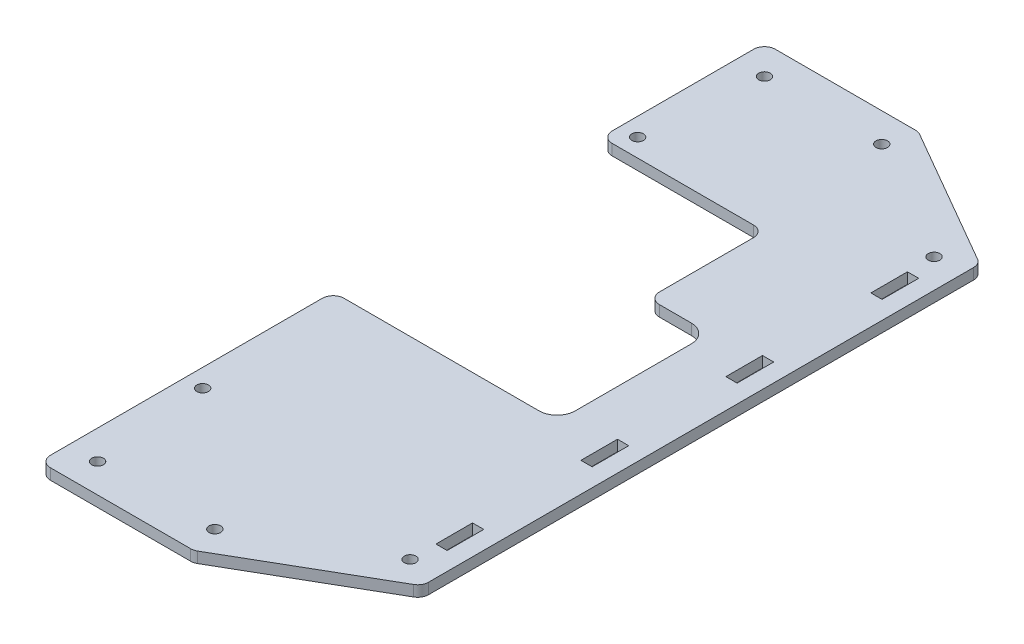
SolidWorks part; units mm, degrees
ref_plane "Front Plane" through (0, 0, 0) normal (0, 0, 1) x (1, 0, 0)
ref_plane "Top Plane" through (0, 0, 0) normal (0, 1, 0) x (1, 0, 0)
ref_plane "Right Plane" through (0, 0, 0) normal (1, 0, 0) x (0, 0, -1)
sketch "Sketch1" plane through (0, 0, 0) normal (0, 1, 0) x (1, 0, 0)
  line L0 (-85, 100) -> (85, 100) construction
  line L1 (-125, 100) -> (125, 100) construction
  line L2 (-125, 100) -> (-125, -100) construction
  line L3 (-125, -100) -> (125, -100) construction
  line L4 (125, 100) -> (125, -100) construction
  line L5 (85, 100) -> (125, 76.906) construction
  line L6 (125, 76.906) -> (125, -76.906) construction
  line L8 (-125, -76.906) -> (-125, 76.906) construction
  line L9 (-125, 76.906) -> (-85, 100) construction
  line L10 (-125, 0) -> (125, 0) construction
  line L11 (85, -100) -> (125, -76.906) construction
  line L12 (-85, -100) -> (85, -100) construction
  line L13 (-125, -76.906) -> (-85, -100) construction
  line L15 (-42.5, 100) -> (42.5, 100) construction
  line L16 (-42.5, 100) -> (-42.5, 65) construction
  line L17 (-42.5, 65) -> (42.5, 65) construction
  line L18 (42.5, 100) -> (42.5, 65) construction
  line L19 (42.5, -100) -> (42.5, -65) construction
  line L20 (-42.5, -65) -> (42.5, -65) construction
  line L21 (-42.5, -100) -> (-42.5, -65) construction
  line L22 (-42.5, -100) -> (42.5, -100) construction
  line L23 (42.5, 100) -> (85, 100)
  line L24 (85, 100) -> (125, 76.906)
  line L25 (125, 76.906) -> (125, -76.906)
  line L26 (125, -76.906) -> (85, -100)
  line L27 (85, -100) -> (42.5, -100)
  line L28 (42.5, 100) -> (42.5, -100)
  line L29 (99.3, 22) -> (67.3, 22) construction
  line L30 (103.3, -14) -> (103.3, 18) construction
  line L31 (63.3, 18) -> (63.3, -14) construction
  line L32 (67.3, -18) -> (99.3, -18) construction
  line L33 (99.3, 22) -> (67.3, 22) construction
  line L34 (103.3, -14) -> (103.3, 18) construction
  line L35 (63.3, 18) -> (63.3, -14) construction
  line L36 (67.3, -18) -> (99.3, -18) construction
  line L37 (99.3, 23) -> (67.3, 23)
  line L38 (62.3, 18) -> (62.3, -14)
  line L39 (67.3, -19) -> (99.3, -19)
  line L40 (104.3, -14) -> (104.3, 18)
  arc A0 (67.3, 22) -> (63.3, 18) centre (67.3, 18) ccw construction
  arc A1 (103.3, 18) -> (99.3, 22) centre (99.3, 18) ccw construction
  arc A2 (63.3, -14) -> (67.3, -18) centre (67.3, -14) ccw construction
  arc A3 (99.3, -18) -> (103.3, -14) centre (99.3, -14) ccw construction
  arc A4 (103.3, 18) -> (99.3, 22) centre (99.3, 18) ccw construction
  arc A5 (67.3, 22) -> (63.3, 18) centre (67.3, 18) ccw construction
  arc A6 (63.3, -14) -> (67.3, -18) centre (67.3, -14) ccw construction
  arc A7 (99.3, -18) -> (103.3, -14) centre (99.3, -14) ccw construction
  arc A8 (104.3, 18) -> (99.3, 23) centre (99.3, 18) ccw
  arc A9 (67.3, 23) -> (62.3, 18) centre (67.3, 18) ccw
  arc A10 (62.3, -14) -> (67.3, -19) centre (67.3, -14) ccw
  arc A11 (99.3, -19) -> (104.3, -14) centre (99.3, -14) ccw
  point P4 (0, 100)
  point P6 (-125, 0)
  point P9 (0, 0)
  point P22 (0, 65)
  dimension "D1" = 250
  dimension "D2" = 200
  dimension "D3" = 60
  dimension "D4" = 60
  dimension "D5" = 40
  dimension "D6" = 85
  dimension "D7" = 35
  dimension "D8" = 1
extrude "Boss-Extrude1" add sketch "Sketch1" along normal blind 3
sketch "Sketch2" plane through (0, 3, 0) normal (0, 1, 0) x (1, 0, 0)
  line L0 (42.5, 100) -> (42.5, -100) construction
  line L1 (42.5, 55) -> (87.5, 55)
  line L2 (42.5, 55) -> (42.5, -19)
  line L3 (42.5, -19) -> (87.5, -19)
  line L4 (87.5, 55) -> (87.5, -19)
  line L5 (67.3, -19) -> (99.3, -19) construction
  dimension "D1" = 74
  dimension "D2" = 45
extrude "Cut-Extrude1" cut sketch "Sketch2" against normal up to next
fillet "Fillet2" radius 3 10 edges at (42.5, 1.5, 19) (42.5, 1.5, 100) (85, 1.5, 100) (125, 1.5, 76.906) (125, 1.5, -76.906) (85, 1.5, -100) (42.5, 1.5, -100) (87.5, 1.5, -55) (42.5, 1.5, -55) (87.5, 1.5, -23)
sketch "Sketch3" plane through (0, 3, 0) normal (0, 1, 0) x (1, 0, 0)
  line L0 (118.45, 14.95) -> (118.45, -14.95) construction
  line L5 (116.9, 14.95) -> (120, 14.95)
  line L6 (116.9, 14.95) -> (116.9, 25.05)
  line L7 (116.9, 25.05) -> (120, 25.05)
  line L8 (120, 14.95) -> (120, 25.05)
  line L9 (116.9, -14.95) -> (120, -14.95)
  line L10 (116.9, -14.95) -> (116.9, -25.05)
  line L11 (116.9, -25.05) -> (120, -25.05)
  line L12 (120, -14.95) -> (120, -25.05)
  line L13 (125, -75.1739) -> (125, 75.1739) construction
  line L14 (116.9, 65.05) -> (120, 65.05)
  line L15 (116.9, 65.05) -> (116.9, 54.95)
  line L16 (116.9, 54.95) -> (120, 54.95)
  line L17 (120, 65.05) -> (120, 54.95)
  line L18 (116.9, -54.95) -> (120, -54.95)
  line L19 (116.9, -54.95) -> (116.9, -65.05)
  line L20 (116.9, -65.05) -> (120, -65.05)
  line L21 (120, -54.95) -> (120, -65.05)
  point P0 (120, 20)
  point P1 (120, -20)
  point P21 (120, 60)
  point P22 (120, -60)
  point P25 (118.45, 0)
  dimension "D1" = 40
  dimension "D2" = 40
  dimension "D3" = 3.1
  dimension "D4" = 10.1
  dimension "D5" = 5
  dimension "D6" = 40
extrude "Cut-Extrude2" cut sketch "Sketch3" against normal through all
sketch "Sketch4" plane through (0, 3, 0) normal (0, 1, 0) x (1, 0, 0)
  line L0 (84.1962, 100) -> (45.5, 100) construction
  line L1 (42.5, 97) -> (42.5, 58) construction
  line L2 (84.5, 55) -> (45.5, 55) construction
  line L4 (42.5, -22) -> (42.5, -97) construction
  line L5 (45.5, -100) -> (84.1962, -100) construction
  line L6 (125, -75.1739) -> (125, 75.1739) construction
  line L7 (123.5, 77.772) -> (85.6962, 99.5981) construction
  line L8 (85.6962, -99.5981) -> (123.5, -77.772) construction
  circle A0 centre (50.5, 92) radius 1.6
  circle A1 centre (47.5, 60) radius 1.6
  circle A2 centre (47.5, -60) radius 1.6
  circle A3 centre (50.5, -92) radius 1.6
  circle A4 centre (117, 72.2872) radius 1.6
  circle A5 centre (117, -72.2872) radius 1.6
  circle A6 centre (82.8564, 92) radius 1.6
  circle A7 centre (82.8564, -92) radius 1.6
  dimension "D1" = 3.2
  dimension "D2" = 8
  dimension "D3" = 8
  dimension "D4" = 5
  dimension "D5" = 5
  dimension "D6" = 5
  dimension "D7" = 40
  dimension "D8" = 8
  dimension "D9" = 8
  dimension "D10" = 8
  dimension "D11" = 8
  dimension "D12" = 8
  dimension "D13" = 8
  dimension "D14" = 8
  dimension "D15" = 8
  dimension "D16" = 8
  dimension "D17" = 8
extrude "Cut-Extrude3" cut sketch "Sketch4" against normal up to next
